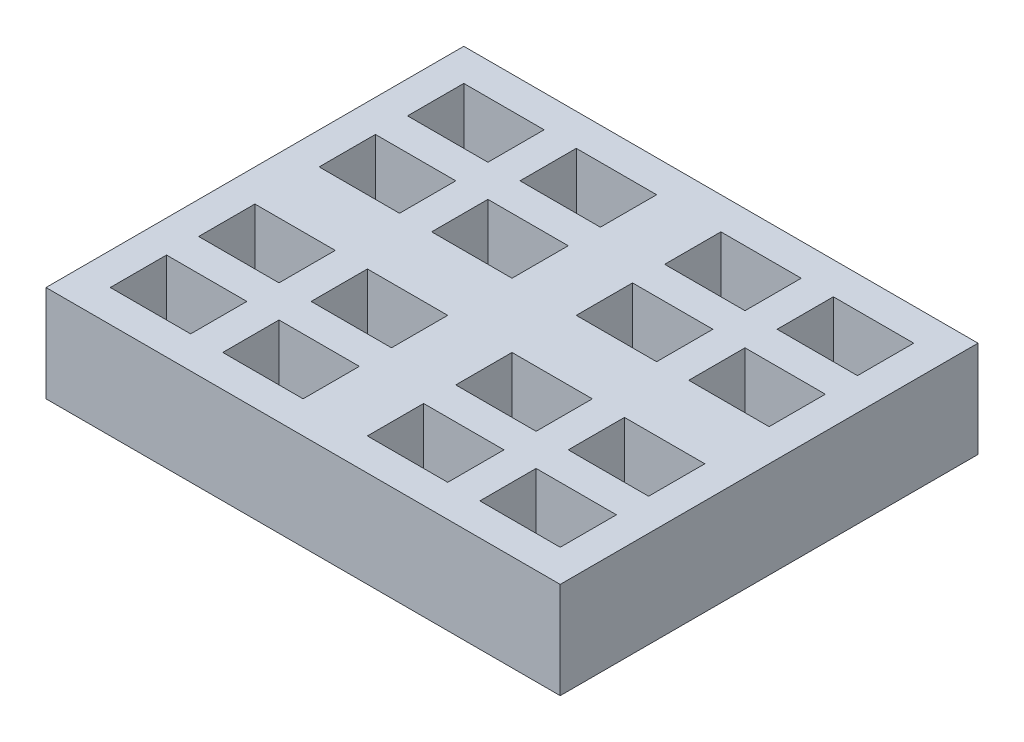
SolidWorks part; units mm, degrees
ref_plane "Front Plane" through (0, 0, 0) normal (0, 0, 1) x (1, 0, 0)
ref_plane "Top Plane" through (0, 0, 0) normal (0, 1, 0) x (1, 0, 0)
ref_plane "Right Plane" through (0, 0, 0) normal (1, 0, 0) x (0, 0, -1)
sketch "Sketch1" plane through (0, 0, 0) normal (0, 1, 0) x (1, 0, 0)
  line L0 (-4.3574, 6.1356) -> (-4.3574, -6.8644) construction
  line L1 (-12.3574, 6.1356) -> (3.6426, 6.1356)
  line L2 (-12.3574, 6.1356) -> (-12.3574, -6.8644)
  line L3 (-12.3574, -6.8644) -> (3.6426, -6.8644)
  line L4 (3.6426, 6.1356) -> (3.6426, -6.8644)
  line L5 (-12.3574, -0.3644) -> (3.6426, -0.3644) construction
  line L6 (-8.3574, 6.1356) -> (-8.3574, -0.3644) construction
  line L11 (-8.3574, 2.8856) -> (-12.3574, 2.8856) construction
  line L12 (-11.3574, 2.3856) -> (-8.8574, 2.3856)
  line L13 (-11.3574, 5.1356) -> (-8.8574, 5.1356)
  line L14 (-11.3574, 5.1356) -> (-11.3574, 3.3856)
  line L15 (-11.3574, 3.3856) -> (-8.8574, 3.3856)
  line L16 (-8.8574, 5.1356) -> (-8.8574, 3.3856)
  line L17 (-8.8574, 0.6356) -> (-8.8574, 2.3856)
  line L18 (-11.3574, 0.6356) -> (-8.8574, 0.6356)
  line L19 (-11.3574, 0.6356) -> (-11.3574, 2.3856)
  line L20 (-5.3574, 0.6356) -> (-5.3574, 2.3856)
  line L21 (-5.3574, 0.6356) -> (-7.8574, 0.6356)
  line L22 (-7.8574, 0.6356) -> (-7.8574, 2.3856)
  line L23 (-5.3574, 2.3856) -> (-7.8574, 2.3856)
  line L24 (-5.3574, 3.3856) -> (-7.8574, 3.3856)
  line L25 (-7.8574, 5.1356) -> (-7.8574, 3.3856)
  line L26 (-5.3574, 5.1356) -> (-7.8574, 5.1356)
  line L27 (-5.3574, 5.1356) -> (-5.3574, 3.3856)
  line L28 (-5.3574, -1.3644) -> (-7.8574, -1.3644)
  line L29 (-7.8574, -1.3644) -> (-7.8574, -3.1144)
  line L30 (-5.3574, -3.1144) -> (-7.8574, -3.1144)
  line L31 (-5.3574, -1.3644) -> (-5.3574, -3.1144)
  line L32 (-11.3574, -1.3644) -> (-11.3574, -3.1144)
  line L33 (-11.3574, -1.3644) -> (-8.8574, -1.3644)
  line L34 (-8.8574, -1.3644) -> (-8.8574, -3.1144)
  line L35 (-11.3574, -3.1144) -> (-8.8574, -3.1144)
  line L36 (-5.3574, -5.8644) -> (-5.3574, -4.1144)
  line L37 (-5.3574, -5.8644) -> (-7.8574, -5.8644)
  line L38 (-7.8574, -5.8644) -> (-7.8574, -4.1144)
  line L39 (-5.3574, -4.1144) -> (-7.8574, -4.1144)
  line L40 (-11.3574, -4.1144) -> (-8.8574, -4.1144)
  line L41 (-8.8574, -5.8644) -> (-8.8574, -4.1144)
  line L42 (-11.3574, -5.8644) -> (-8.8574, -5.8644)
  line L43 (-11.3574, -5.8644) -> (-11.3574, -4.1144)
  line L44 (-3.3574, -5.8644) -> (-0.8574, -5.8644)
  line L45 (-0.8574, -5.8644) -> (-0.8574, -4.1144)
  line L46 (-3.3574, -4.1144) -> (-0.8574, -4.1144)
  line L47 (-3.3574, -5.8644) -> (-3.3574, -4.1144)
  line L48 (2.6426, -5.8644) -> (2.6426, -4.1144)
  line L49 (2.6426, -5.8644) -> (0.1426, -5.8644)
  line L50 (0.1426, -5.8644) -> (0.1426, -4.1144)
  line L51 (2.6426, -4.1144) -> (0.1426, -4.1144)
  line L52 (-3.3574, -1.3644) -> (-3.3574, -3.1144)
  line L53 (-3.3574, -3.1144) -> (-0.8574, -3.1144)
  line L54 (-0.8574, -1.3644) -> (-0.8574, -3.1144)
  line L55 (-3.3574, -1.3644) -> (-0.8574, -1.3644)
  line L56 (2.6426, -1.3644) -> (0.1426, -1.3644)
  line L57 (0.1426, -1.3644) -> (0.1426, -3.1144)
  line L58 (2.6426, -3.1144) -> (0.1426, -3.1144)
  line L59 (2.6426, -1.3644) -> (2.6426, -3.1144)
  line L60 (-3.3574, 0.6356) -> (-0.8574, 0.6356)
  line L61 (-0.8574, 0.6356) -> (-0.8574, 2.3856)
  line L62 (-3.3574, 2.3856) -> (-0.8574, 2.3856)
  line L63 (-3.3574, 0.6356) -> (-3.3574, 2.3856)
  line L64 (2.6426, 0.6356) -> (2.6426, 2.3856)
  line L65 (2.6426, 0.6356) -> (0.1426, 0.6356)
  line L66 (0.1426, 0.6356) -> (0.1426, 2.3856)
  line L67 (2.6426, 2.3856) -> (0.1426, 2.3856)
  line L68 (-3.3574, 5.1356) -> (-3.3574, 3.3856)
  line L69 (-3.3574, 5.1356) -> (-0.8574, 5.1356)
  line L70 (-0.8574, 5.1356) -> (-0.8574, 3.3856)
  line L71 (-3.3574, 3.3856) -> (-0.8574, 3.3856)
  line L72 (2.6426, 3.3856) -> (0.1426, 3.3856)
  line L73 (0.1426, 5.1356) -> (0.1426, 3.3856)
  line L74 (2.6426, 5.1356) -> (0.1426, 5.1356)
  line L75 (2.6426, 5.1356) -> (2.6426, 3.3856)
  dimension "D1" = 16
  dimension "D2" = 13
  dimension "D3" = 4
  dimension "D4" = 1
  dimension "D5" = 0.5
  dimension "D6" = 1
  dimension "D7" = 0.5
extrude "Boss-Extrude1" add sketch "Sketch1" along normal blind 3
